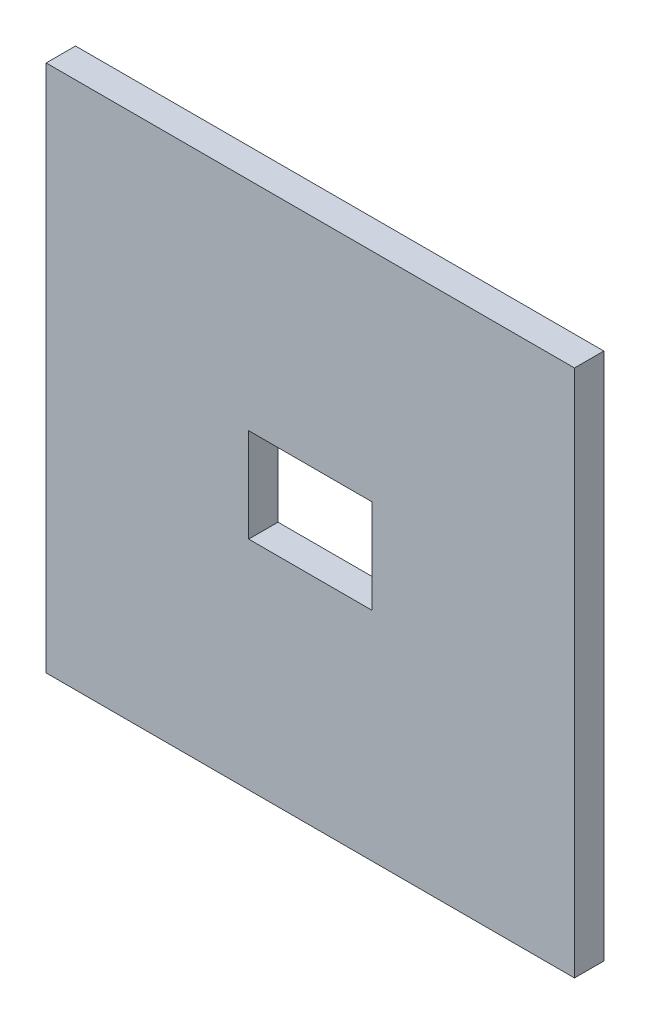
SolidWorks part; units mm, degrees
ref_plane "Alzado" through (0, 0, 0) normal (0, 0, 1) x (1, 0, 0)
ref_plane "Planta" through (0, 0, 0) normal (0, 1, 0) x (1, 0, 0)
ref_plane "Vista lateral" through (0, 0, 0) normal (1, 0, 0) x (0, 0, -1)
ref_plane "Plane1" through (0, 0, 0) normal (0, 0, -1) x (-1, 0, 0)
sketch "Sketch1" plane through (0, 0, 0) normal (0, 0, -1) x (-1, 0, 0)
  line L0 (-10.5, 8) -> (10.5, 8)
  line L1 (10.5, 8) -> (10.5, -8)
  line L2 (10.5, -8) -> (-10.5, -8)
  line L3 (-10.5, -8) -> (-10.5, 8)
  line L4 (-45, 45) -> (-45, -45)
  line L5 (-45, -45) -> (45, -45)
  line L6 (45, -45) -> (45, 45)
  line L7 (45, 45) -> (-45, 45)
  line L8 (0, 45) -> (0, -45) construction
  line L9 (-45, 0) -> (45, 0) construction
  point P12 (0, 0)
  dimension "D1" = 90
  dimension "D2" = 90
  dimension "D3" = 16
  dimension "D4" = 21
  dimension "D5" = 8
  dimension "D6" = 10.5
extrude "Boss-Extrude1" add sketch "Sketch1" against normal blind 5
